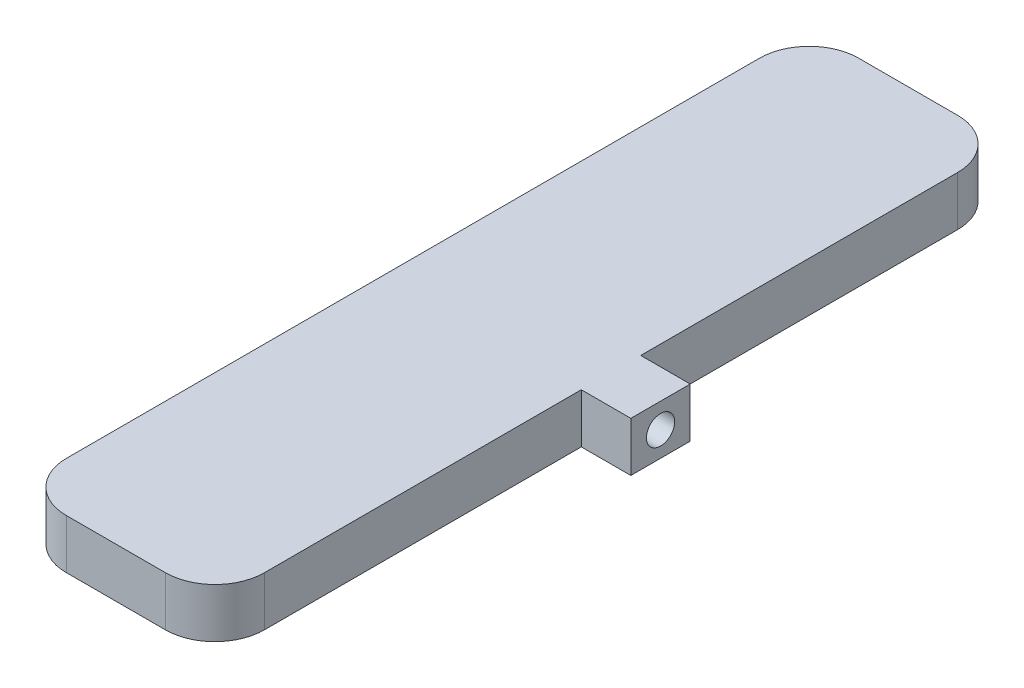
SolidWorks part; units mm, degrees
ref_plane "Front Plane" through (0, 0, 0) normal (0, 0, 1) x (1, 0, 0)
ref_plane "Top Plane" through (0, 0, 0) normal (0, 1, 0) x (1, 0, 0)
ref_plane "Right Plane" through (0, 0, 0) normal (1, 0, 0) x (0, 0, -1)
sketch "Sketch1" plane through (0, 0, 0) normal (0, 1, 0) x (1, 0, 0)
  line L1 (-10, 40) -> (10, 40)
  line L2 (-10, 40) -> (-10, -40)
  line L3 (-10, -40) -> (10, -40)
  line L4 (10, 40) -> (10, -40)
  line L5 (-10, 40) -> (10, -40) construction
  line L6 (-10, -40) -> (10, 40) construction
  point P0 (0, 0)
  dimension "D1" = 20
  dimension "D2" = 80
extrude "Boss-Extrude1" add sketch "Sketch1" along normal blind 5
fillet "Fillet1" radius 5 4 edges at (-10, 2.5, -40) (10, 2.5, -40) (-10, 2.5, 40) (10, 2.5, 40)
shell "Shell1" thickness 2
sketch "Sketch2" plane through (10, 0, 0) normal (1, 0, 0) x (0, 0, -1)
  line L0 (-35, 0) -> (35, 0) construction
  line L1 (-3, 0) -> (3, 0)
  line L2 (-3, 0) -> (-3, 5)
  line L3 (-3, 5) -> (3, 5)
  line L4 (3, 0) -> (3, 5)
  line L5 (-35, 5) -> (35, 5) construction
  point P8 (0, 5)
  point P9 (0, 0)
  dimension "D1" = 6
extrude "Boss-Extrude2" add sketch "Sketch2" along normal blind 5
sketch "Sketch3" plane through (15, 0, 0) normal (1, 0, 0) x (0, 0, -1)
  line L0 (-3, 0) -> (3, 0) construction
  line L1 (-3, 5) -> (-3, 0) construction
  circle A0 centre (0, 2.5) radius 1.425
  point P5 (0, 0)
  point P8 (-3, 2.5)
  dimension "D1" = 2.85
extrude "Cut-Extrude1" cut sketch "Sketch3" against normal blind 4
